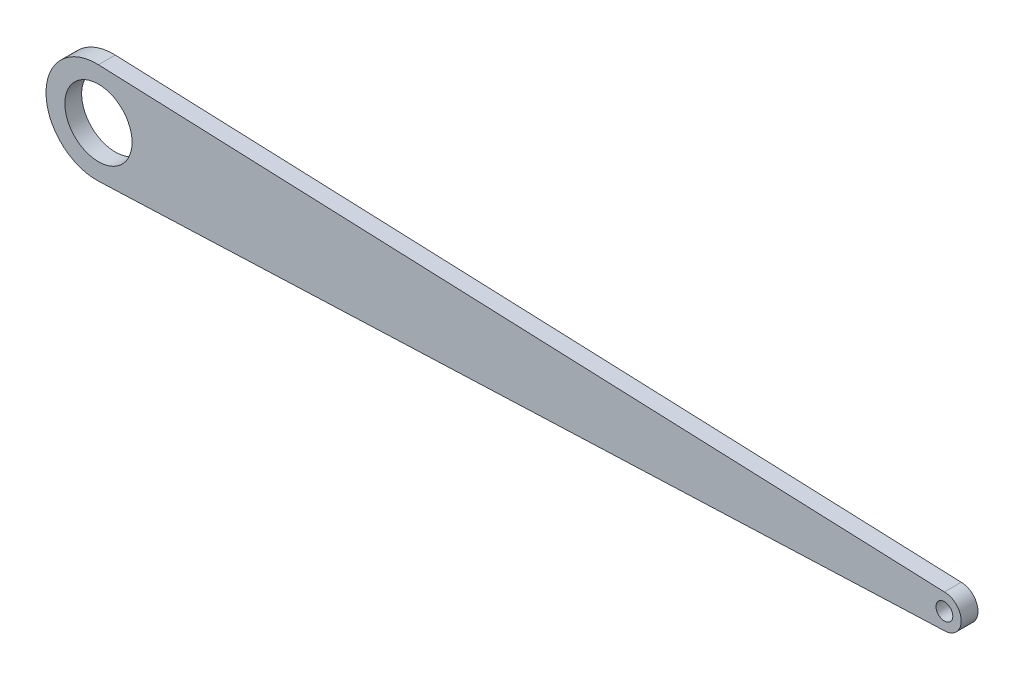
SolidWorks part; units mm, degrees
ref_plane "Plano frontal" through (0, 0, 0) normal (0, 0, 1) x (1, 0, 0)
ref_plane "Plano superior" through (0, 0, 0) normal (0, 1, 0) x (1, 0, 0)
ref_plane "Plano direito" through (0, 0, 0) normal (1, 0, 0) x (0, 0, -1)
sketch "Esboço1" plane through (0, 0, 0) normal (0, 0, 1) x (1, 0, 0)
  line L1 (-125.781, 0) -> (125.899, 0) construction
  line L6 (-125.781, 15) -> (125.899, 5)
  line L9 (125.899, -5) -> (-125.781, -15)
  circle A3 centre (125.899, 0) radius 2.5
  circle A4 centre (-125.781, 0) radius 10
  arc A5 (-125.781, 15) -> (-125.781, -15) centre (-126.377, 0) ccw
  arc A7 (125.899, 5) -> (125.899, -5) centre (125.899, 0) cw
  point P3 (0.059, 5)
  dimension "D1" = 251.68
extrude "Ressalto-extrusão1" add sketch "Esboço1" along normal blind 5
